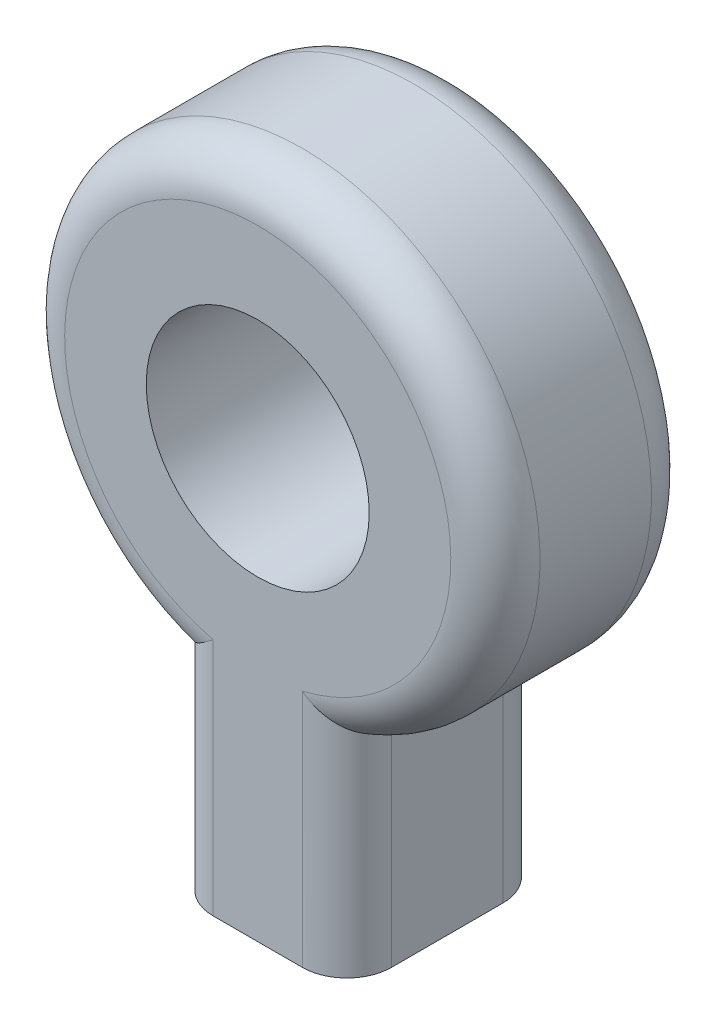
SolidWorks part; units mm, degrees
ref_plane "Front Plane" through (0, 0, 0) normal (0, 0, 1) x (1, 0, 0)
ref_plane "Top Plane" through (0, 0, 0) normal (0, 1, 0) x (1, 0, 0)
ref_plane "Right Plane" through (0, 0, 0) normal (1, 0, 0) x (0, 0, -1)
sketch "Sketch1" plane through (0, 0, 0) normal (0, 0, 1) x (1, 0, 0)
  line L2 (84.265, 0) -> (0, 0) construction
  line L3 (0, 65.2374) -> (0, 18.1048) construction
  line L8 (0, 9.6034) -> (39.0836, 9.6034) construction
  line L9 (-3.9963, 18.8822) -> (-3.9963, 9.6034)
  line L10 (-3.9963, 9.6034) -> (0, 9.6034)
  line L11 (0, 9.6034) -> (4, 9.6034)
  line L12 (4, 9.6034) -> (4, 18.8838)
  line L13 (0, 9.6034) -> (0, -100.5743) construction
  circle A0 centre (0, 28.7651) radius 5
  arc A2 (4, 18.8838) -> (-3.9963, 18.8822) centre (0, 28.7651) ccw
extrude "Boss-Extrude1" add sketch "Sketch1" along normal blind 9
fillet "Fillet1" radius 2 6 edges at (4, 14.2436, 0) (-0.002, 39.4253, 0) (-3.9963, 14.2428, 0) (-3.9963, 14.2428, 9) (4, 14.2436, 9) (-0.002, 39.4253, 9)
sketch "Sketch2" plane through (0, 9.6034, 0) normal (0, -1, 0) x (1, 0, 0)
  line L0 (-12.9524, 4.5691) -> (-3, 4.5691)
  line L1 (0, 7.5691) -> (0, 8.8165) construction
  line L2 (3, 4.5691) -> (4.6094, 4.5691)
  circle A0 centre (0, 4.5691) radius 3
  point P3 (-4.1715, 4.5691)
extrude "Cut-Extrude2" cut sketch "Sketch2" against normal blind 9 contours A0 L0
